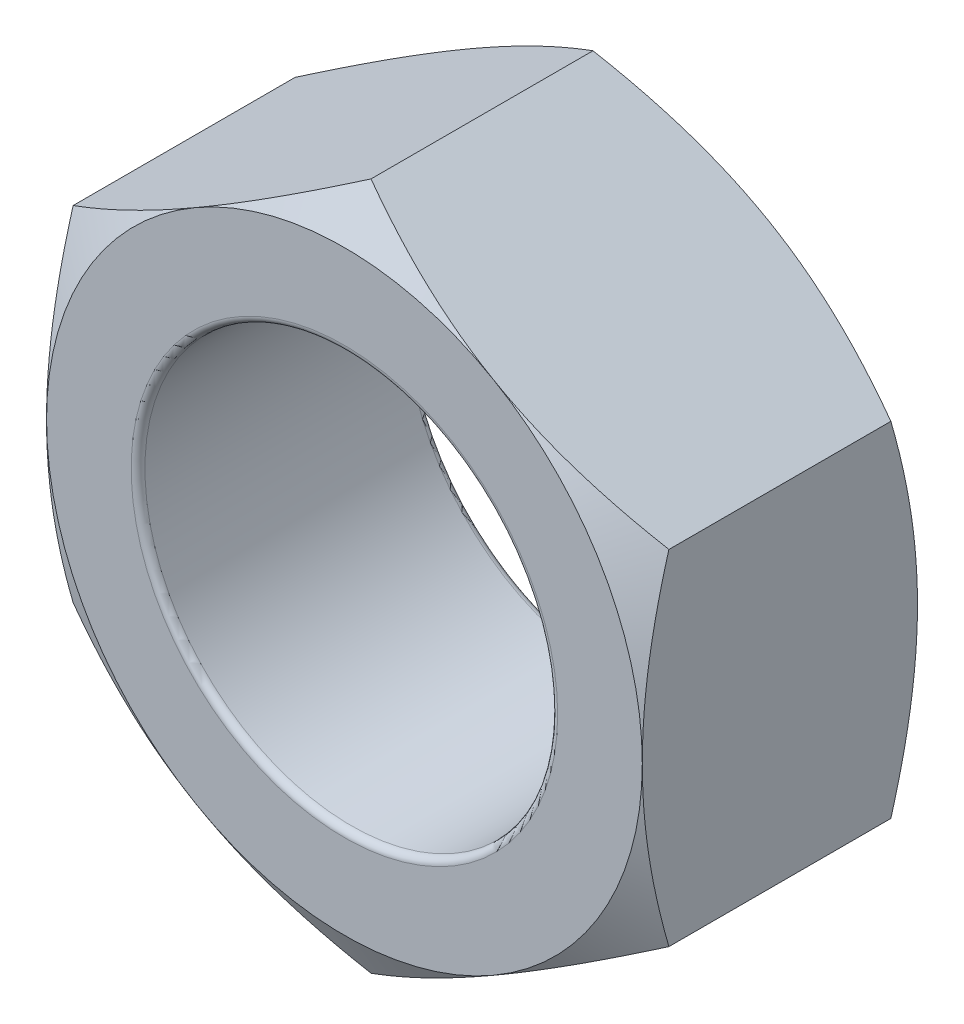
SolidWorks part; units mm, degrees
ref_plane "Front Plane" through (0, 0, 0) normal (0, 0, 1) x (1, 0, 0)
ref_plane "Top Plane" through (0, 0, 0) normal (0, 1, 0) x (1, 0, 0)
ref_plane "Right Plane" through (0, 0, 0) normal (1, 0, 0) x (0, 0, -1)
sketch "Sketch1" plane through (0, 0, 0) normal (0, 0, 1) x (1, 0, 0)
  line L1 (0, 2.5) -> (-2.1651, 1.25)
  line L2 (-2.1651, 1.25) -> (-2.1651, -1.25)
  line L3 (-2.1651, -1.25) -> (0, -2.5)
  line L4 (0, -2.5) -> (2.1651, -1.25)
  line L5 (2.1651, -1.25) -> (2.1651, 1.25)
  line L6 (2.1651, 1.25) -> (0, 2.5)
  circle A0 centre (0, 0) radius 1.5
  circle A1 centre (0, 0) radius 2.1651 construction
  dimension "D1" = 3
  dimension "D2" = 5
extrude "Boss-Extrude1" add sketch "Sketch1" along normal blind 2
sketch "Sketch7" plane through (0, 0, 2) normal (0, 0, 1) x (1, 0, 0)
  circle A0 centre (0, 0) radius 2.1651 construction
  circle A1 centre (0, 0) radius 2.1651
extrude "Cut-Extrude1" cut sketch "Sketch7" against normal blind 2 draft 60 flip side to cut
sketch "Sketch9" plane through (0, 0, 0) normal (0, 0, -1) x (-1, 0, 0)
  circle A0 centre (0, 0) radius 2.1651 construction
  circle A1 centre (0, 0) radius 2.1651
extrude "Cut-Extrude2" cut sketch "Sketch9" against normal blind 2 draft 60 flip side to cut
fillet "Fillet1" radius 0.05 2 edges at (1.5, 0, 2) (1.5, 0, 0)
